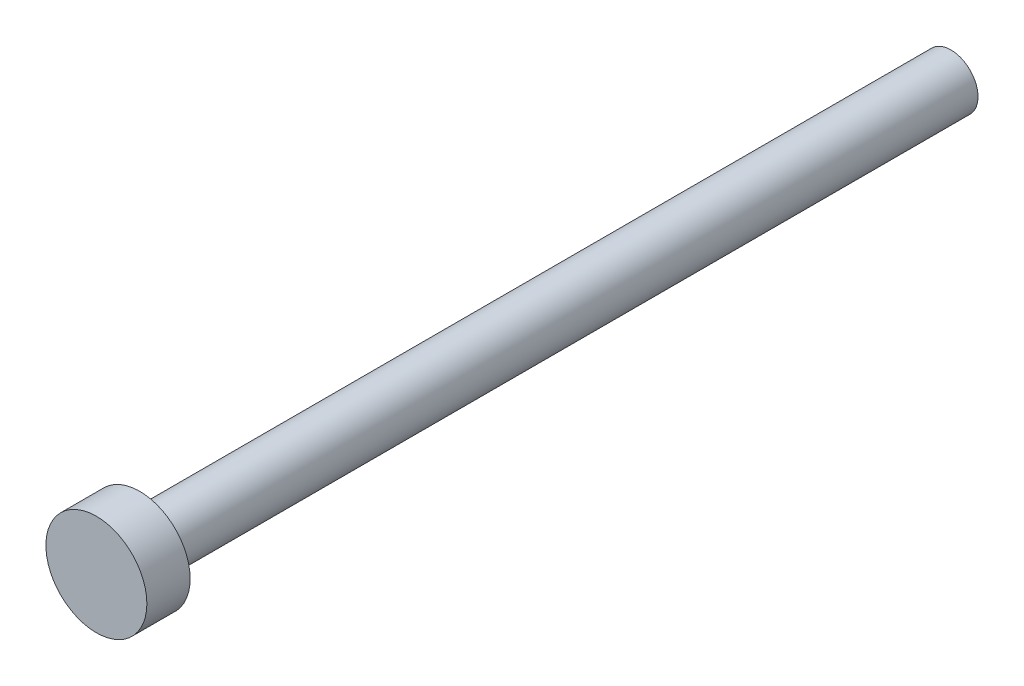
SolidWorks part; units mm, degrees
ref_plane "Plan de face" through (0, 0, 0) normal (0, 0, 1) x (1, 0, 0)
ref_plane "Plan de dessus" through (0, 0, 0) normal (0, 1, 0) x (1, 0, 0)
ref_plane "Plan de droite" through (0, 0, 0) normal (1, 0, 0) x (0, 0, -1)
sketch "Esquisse1" plane through (0, 0, 0) normal (0, 0, 1) x (1, 0, 0)
  circle A0 centre (0, 0) radius 2.8
  dimension "D1" = 5.6
extrude "Boss.-Extru.1" add sketch "Esquisse1" along normal blind 2.4
sketch "Esquisse2" plane through (0, 0, 0) normal (0, 0, -1) x (-1, 0, 0)
  circle A0 centre (0, 0) radius 1.5
  dimension "D1" = 3
extrude "Boss.-Extru.2" add sketch "Esquisse2" along normal blind 45
